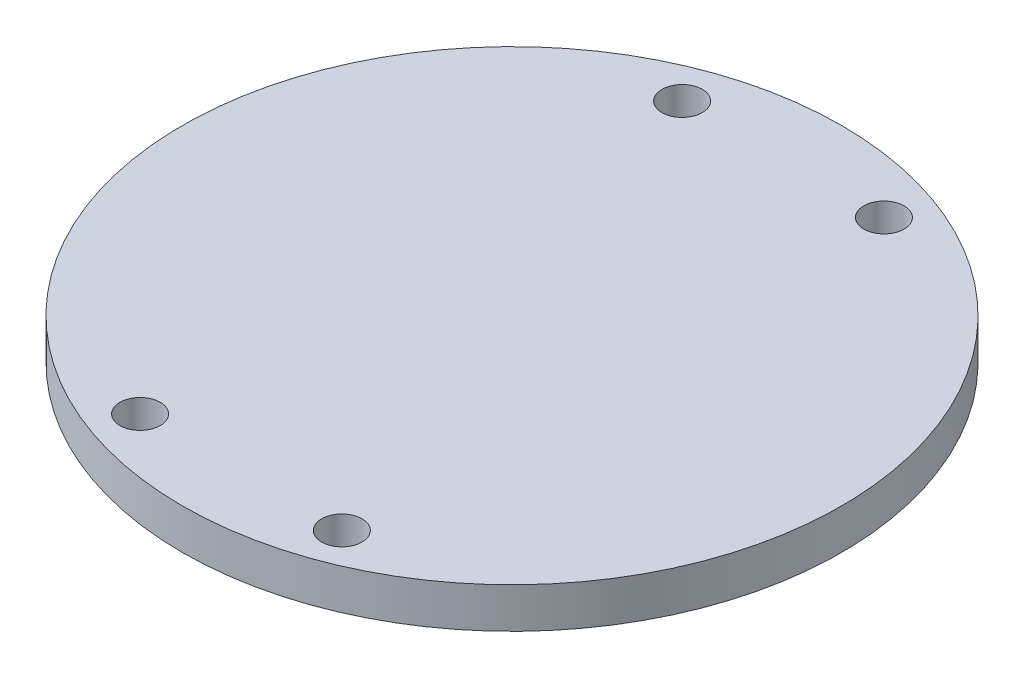
SolidWorks part; units mm, degrees
ref_plane "Front Plane" through (0, 0, 0) normal (0, 0, 1) x (1, 0, 0)
ref_plane "Top Plane" through (0, 0, 0) normal (0, 1, 0) x (1, 0, 0)
ref_plane "Right Plane" through (0, 0, 0) normal (1, 0, 0) x (0, 0, -1)
sketch "Sketch1" plane through (0, 0, 0) normal (0, 1, 0) x (1, 0, 0)
  circle A0 centre (0, 0) radius 49
  dimension "D1" = 98
extrude "Boss-Extrude1" add sketch "Sketch1" along normal blind 6
sketch "Sketch2" plane through (0, 6, 0) normal (0, 1, 0) x (1, 0, 0)
  circle A1 centre (-15, 40.2989) radius 3
  circle A2 centre (15, 40.2989) radius 3
  circle A3 centre (-15, -40.2989) radius 3
  circle A4 centre (15, -40.2989) radius 3
  arc A5 (-17.7733, 39.1549) -> (-17.7733, -39.1549) centre (0, 0) ccw
  arc A6 (12.1537, 41.2467) -> (-12.1537, 41.2467) centre (0, 0) ccw
  arc A7 (17.7733, -39.1549) -> (17.7733, 39.1549) centre (0, 0) ccw
  arc A8 (-12.1537, -41.2467) -> (12.1537, -41.2467) centre (0, 0) ccw
  dimension "D2" = 6
  dimension "D3" = 6
  dimension "D4" = 6
  dimension "D5" = 6
  dimension "D6" = 86
  dimension "D7" = 30
  dimension "D8" = 30
  dimension "D9" = 15
  dimension "D10" = 15
extrude "Cut-Extrude2" cut sketch "Sketch2" against normal blind 6 contours A1 | A2 | A4 | A3 A5
